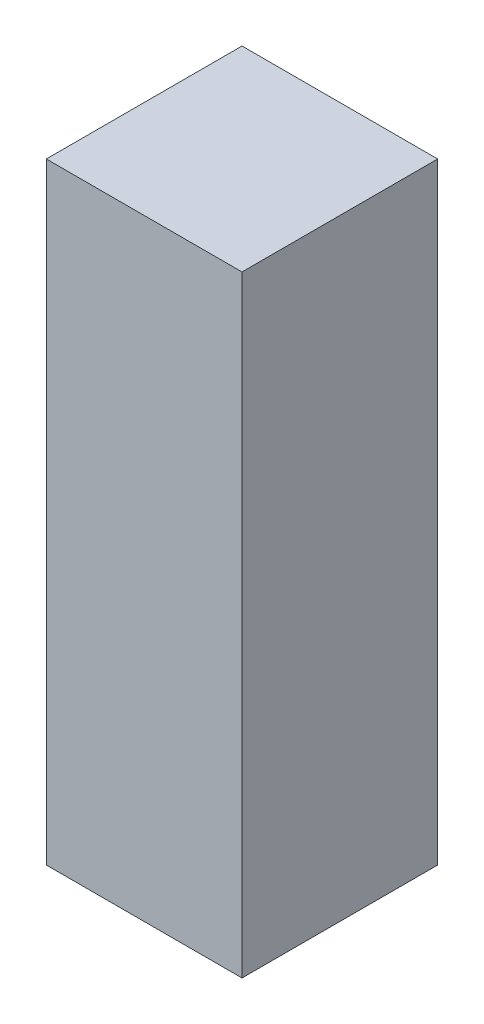
SolidWorks part; units mm, degrees
ref_plane "Front Plane" through (0, 0, 0) normal (0, 0, 1) x (1, 0, 0)
ref_plane "Top Plane" through (0, 0, 0) normal (0, 1, 0) x (1, 0, 0)
ref_plane "Right Plane" through (0, 0, 0) normal (1, 0, 0) x (0, 0, -1)
sketch "Sketch1" plane through (0, 0, 0) normal (0, 1, 0) x (1, 0, 0)
  line L1 (-51.7258, 52.1652) -> (28.2742, 52.1652)
  line L2 (-51.7258, 52.1652) -> (-51.7258, -27.8348)
  line L3 (-51.7258, -27.8348) -> (28.2742, -27.8348)
  line L4 (28.2742, 52.1652) -> (28.2742, -27.8348)
  dimension "D1" = 80
  dimension "D2" = 80
extrude "Boss-Extrude1" add sketch "Sketch1" along normal blind 250
